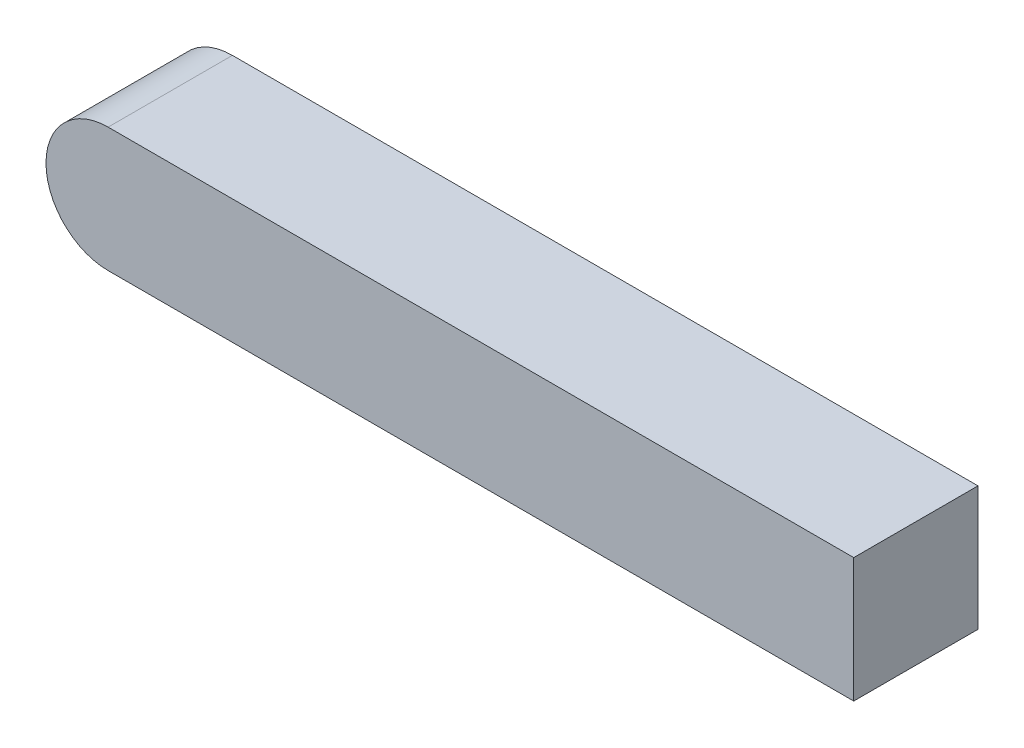
SolidWorks part; units mm, degrees
ref_plane "Plano frontal" through (0, 0, 0) normal (0, 0, 1) x (1, 0, 0)
ref_plane "Plano superior" through (0, 0, 0) normal (0, 1, 0) x (1, 0, 0)
ref_plane "Plano direito" through (0, 0, 0) normal (1, 0, 0) x (0, 0, -1)
sketch "Sketch1" plane through (0, 0, 0) normal (0, 0, 1) x (1, 0, 0)
  line L6 (48, -4) -> (48, 4)
  line L7 (48, 4) -> (0, 4)
  line L8 (0, -4) -> (48, -4)
  arc A2 (0, 4) -> (0, -4) centre (0, 0) ccw
  dimension "D3" = 4
  dimension "D1" = 48
  dimension "D2" = 8
extrude "Boss-Extrude1" add sketch "Sketch1" along normal blind 8
